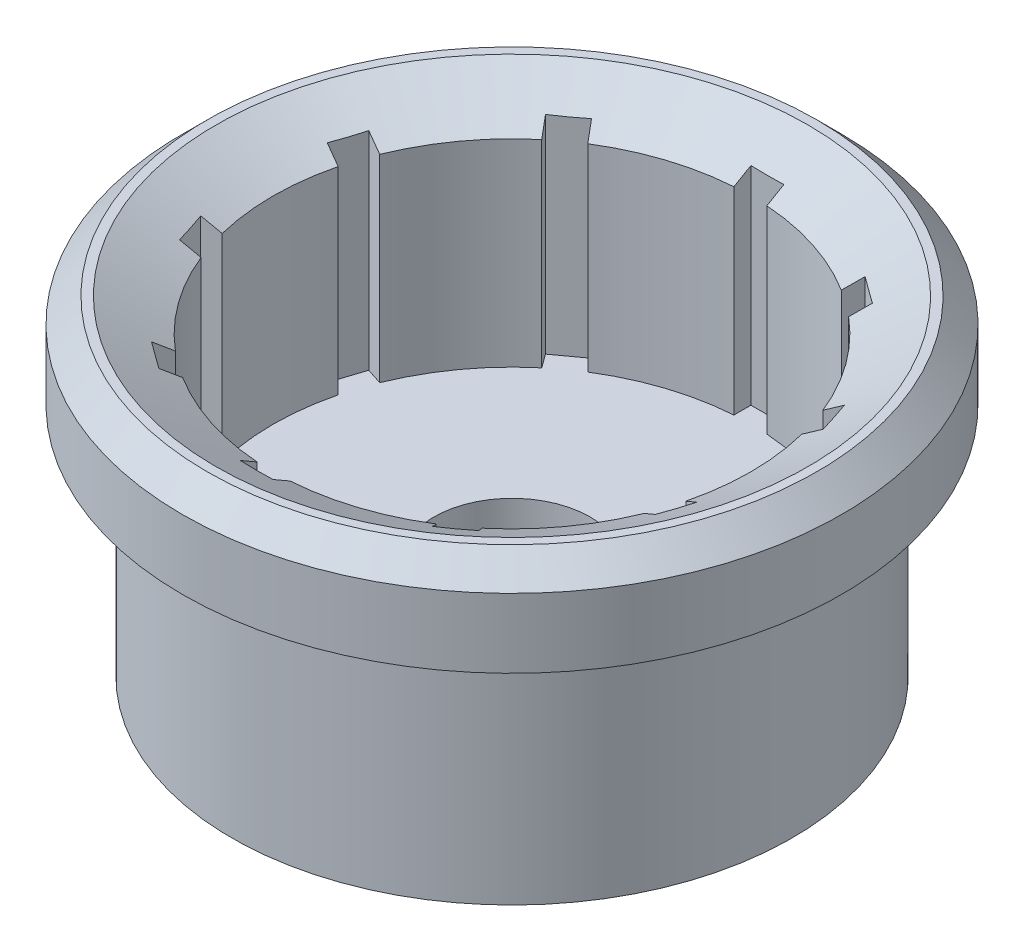
SolidWorks part; units mm, degrees
material "POM 乙缩醛共聚物"
ref_plane "前视基准面" through (0, 0, 0) normal (0, 0, 1) x (1, 0, 0)
ref_plane "上视基准面" through (0, 0, 0) normal (0, 1, 0) x (1, 0, 0)
ref_plane "右视基准面" through (0, 0, 0) normal (1, 0, 0) x (0, 0, -1)
sketch "草图1" plane through (0, 0, 0) normal (0, 0, 1) x (1, 0, 0)
  line L0 (0, 0) -> (-4.4767, 0) construction
  line L1 (0, 0) -> (0, 28.0423) construction
  line L2 (-2.5, 0) -> (-2.5, 8)
  line L3 (-2.5, 8) -> (-4.75, 8)
  line L4 (-4.75, 8) -> (-4.75, 12)
  line L5 (-4.75, 12) -> (-14.5, 12)
  line L6 (-14.5, 12) -> (-14.5, 26)
  line L7 (-14.5, 26) -> (-20, 26)
  line L8 (-20, 26) -> (-20, 20.3)
  line L9 (-20, 20.3) -> (-17, 20.3)
  line L10 (-17, 20.3) -> (-17, 6)
  line L11 (-17, 6) -> (-6.5, 6)
  line L12 (-6.5, 6) -> (-6.5, 5)
  line L13 (-6.5, 5) -> (-4.5, 5)
  line L14 (-4.5, 5) -> (-4.5, 0)
  line L15 (-4.5, 0) -> (-2.5, 0)
  dimension "D1" = 5
  dimension "D2" = 9
  dimension "D3" = 2
  dimension "D4" = 6
  dimension "D5" = 3
  dimension "D6" = 9.5
  dimension "D7" = 4
  dimension "D8" = 1
  dimension "D9" = 34
  dimension "D10" = 40
  dimension "D11" = 5.7
  dimension "D12" = 29
  dimension "D13" = 14
revolve "旋转1" add sketch "草图1" angle 360 about L1
chamfer "倒角1" distance 2 angle 60 1 edges at (0, 26, -14.5)
chamfer "倒角2" distance 1.5 angle 45 1 edges at (0, 26, -20)
sketch "草图2" plane through (0, 12, 0) normal (0, 1, 0) x (1, 0, 0)
  line L1 (1, -15.5) -> (-1, -15.5)
  line L2 (1, -15.5) -> (1, 15.5)
  line L3 (1, 15.5) -> (-1, 15.5)
  line L4 (-1, -15.5) -> (-1, 15.5)
  line L5 (1, -15.5) -> (-1, 15.5) construction
  line L6 (1, 15.5) -> (-1, -15.5) construction
  point P5 (0, 0)
  dimension "D1" = 2
  dimension "D2" = 31
extrude "切除-拉伸1" cut sketch "草图2" along normal through all
pattern_circular "阵列(圆周)1" count 10 over 360 about axis through (0, 0, 0) along (0, 1, 0) of "切除-拉伸1"
chamfer "倒角3" distance 1 angle 45 1 edges at (0, 0, -4.5)
chamfer "倒角4" distance 0.2 angle 45 1 edges at (0, 5, -6.5)
sketch "草图3" plane through (0, 12, 0) normal (0, 1, 0) x (1, 0, 0)
  arc A0 (2.2287, 7.2015) -> (5.0644, -5.584) centre (0, 0) cw construction
  text T0 "LGR 2023/5/16" font "微软雅黑" height 1.5
  point P3 (-3.5903, -7.9534)
  point P5 (0, 0)
  point P6 (0, 0)
  point P7 (0, 0)
  point P9 (4.7707, -5.8716)
extrude "切除-拉伸2" cut sketch "草图3" against normal blind 0.3
